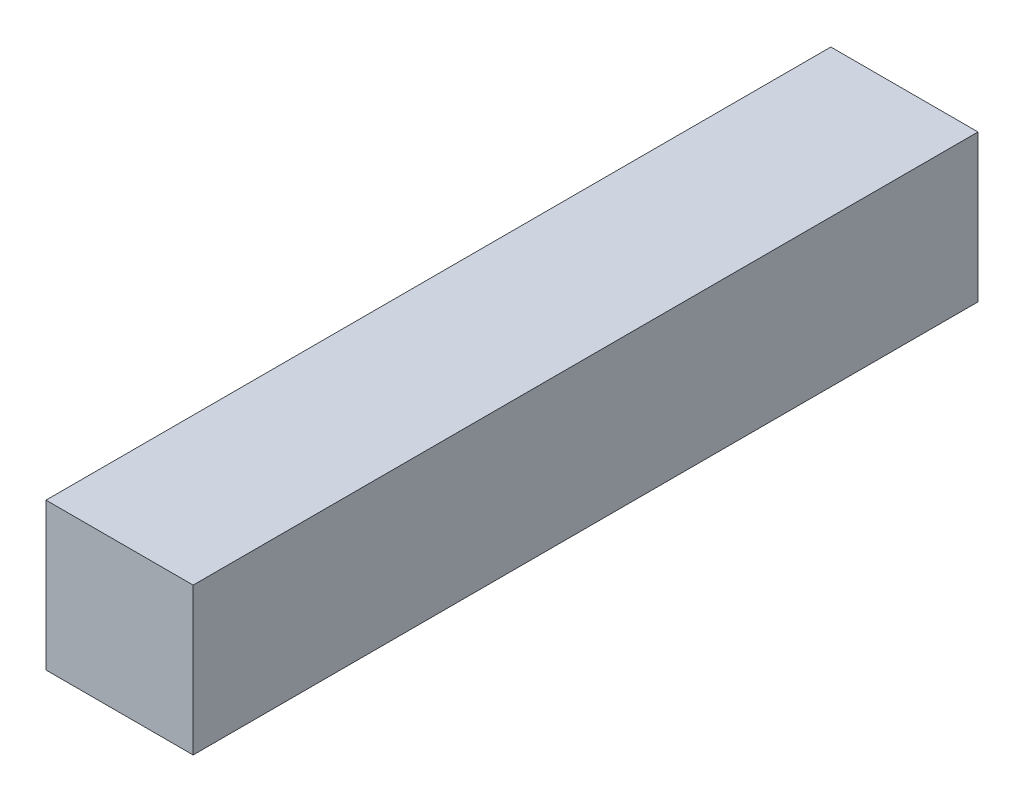
SolidWorks part; units mm, degrees
other "Imported1" parameters "D1"=113.1112, "Length"=113.1112, "Width"=2.3813, "D2"=51.1131, "Height"=2.3813
ref_plane "Front Plane" through (0, 0, 0) normal (0, 0, 1) x (1, 0, 0)
ref_plane "Top Plane" through (0, 0, 0) normal (0, 1, 0) x (1, 0, 0)
ref_plane "Right Plane" through (0, 0, 0) normal (1, 0, 0) x (0, 0, -1)
sketch "Sketch1" plane through (0, 0, 0) normal (0, 0, 1) x (1, 0, 0)
  line L0 (-1.1906, 1.1906) -> (1.1906, -1.1906) construction
  line L1 (-1.1906, 1.1906) -> (1.1906, 1.1906) construction
  line L2 (-1.1906, 1.1906) -> (-1.1906, -1.1906) construction
  line L3 (-1.1906, -1.1906) -> (1.1906, -1.1906) construction
  line L4 (1.1906, 1.1906) -> (1.1906, -1.1906) construction
sketch "Sketch2" plane through (0, 0, 0) normal (1, 0, 0) x (0, 0, -1)
  line L0 (6.35, 0) -> (-6.35, 0) construction
  line L1 (-6.35, 0) -> (-6.35, 1.1906) construction
  line L2 (-6.35, 1.1906) -> (6.35, 1.1906) construction
  line L3 (6.35, 1.1906) -> (6.35, 0) construction
  line L4 (0.7938, 0) -> (0.7938, 1.1906) construction
  line L5 (0.7938, 0) -> (-0.7938, 0) construction
  line L6 (-0.7938, 0) -> (-0.7938, 1.1906) construction
  point P2 (0, 1.1906)
  dimension "Length" = 12.7
  dimension "D1" = 7.1437
sketch "Sketch3" plane through (0, 0, 0) normal (0, 0, 1) x (1, 0, 0)
  line L0 (-1.1906, 1.1906) -> (1.1906, 1.1906)
  line L1 (1.1906, 1.1906) -> (1.1906, -1.1906)
  line L2 (1.1906, -1.1906) -> (-1.1906, -1.1906)
  line L3 (-1.1906, -1.1906) -> (-1.1906, 1.1906)
extrude "Boss-Extrude1" add sketch "Sketch3" along normal up to vertex (6.35 mm away) and the other way up to vertex (6.35 mm away) up to point (0, 0, 6.35) other way up to point (0, 0, -6.35)
equation "\"D1@Sketch2\"=\"Height@Sketch1\"*3"
